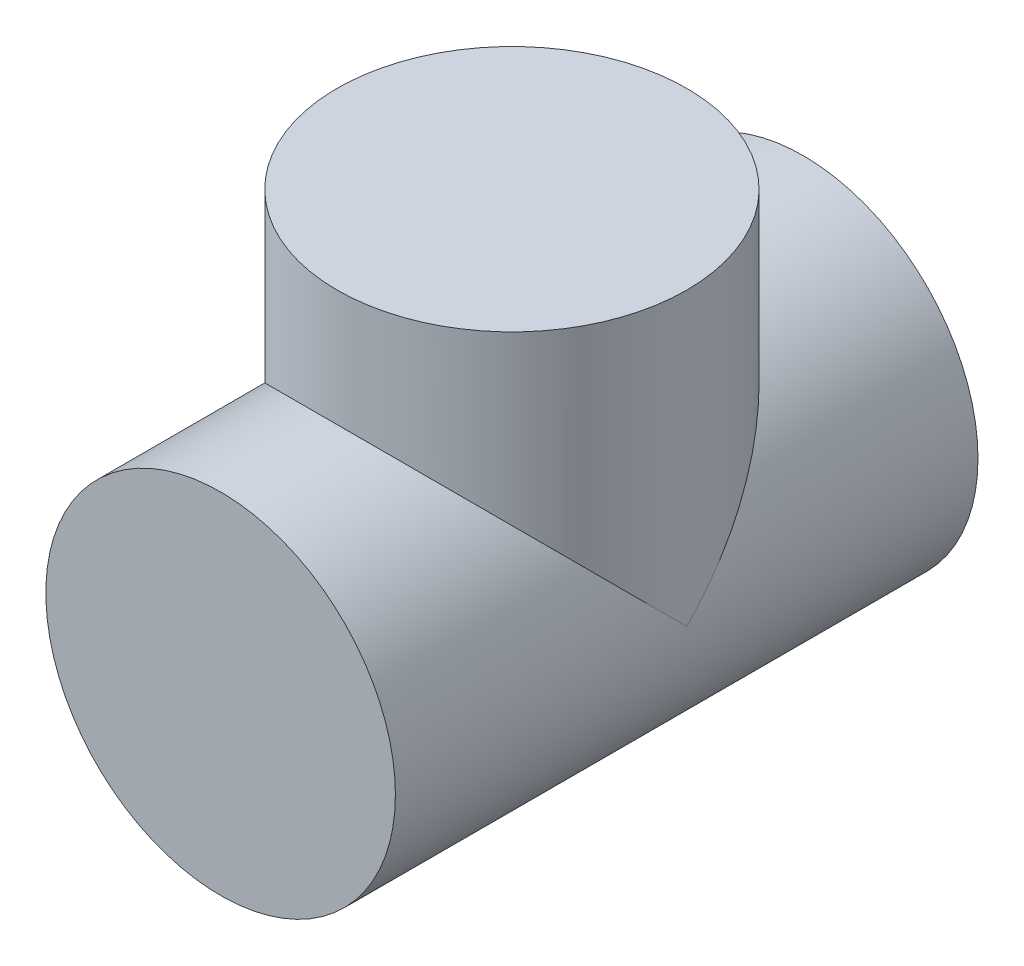
SolidWorks part; units mm, degrees
ref_plane "Front" through (0, 0, 0) normal (0, 0, 1) x (1, 0, 0)
ref_plane "Top" through (0, 0, 0) normal (0, 1, 0) x (1, 0, 0)
ref_plane "Right" through (0, 0, 0) normal (1, 0, 0) x (0, 0, -1)
sketch "Sketch1" plane through (0, 0, 0) normal (0, 0, 1) x (1, 0, 0)
  circle A0 centre (0, 0) radius 7.62
extrude "Boss-Extrude1" add sketch "Sketch1" along normal blind 25.4
sketch "Sketch2" plane through (0, 0, 0) normal (0, 1, 0) x (1, 0, 0)
  line L0 (0, 0) -> (0, -12.7)
  circle A0 centre (0, -12.7) radius 7.62
extrude "Boss-Extrude2" add sketch "Sketch2" along normal blind 12.7
